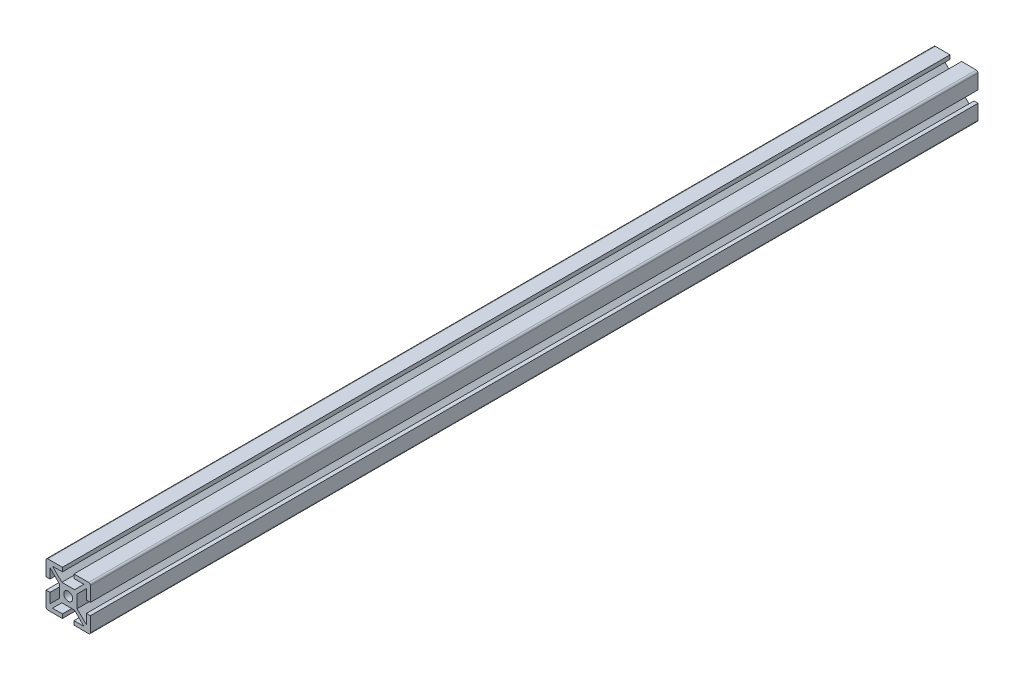
SolidWorks part; units mm, degrees
ref_plane "Front Plane" through (0, 0, 0) normal (0, 0, 1) x (1, 0, 0)
ref_plane "Top Plane" through (0, 0, 0) normal (0, 1, 0) x (1, 0, 0)
ref_plane "Right Plane" through (0, 0, 0) normal (1, 0, 0) x (0, 0, -1)
sketch "Sketch1" plane through (0, 0, 0) normal (0, 0, 1) x (1, 0, 0)
  line L0 (0, 17.7179) -> (0, -17.7179) construction
  line L1 (22.6216, 0) -> (-22.6216, 0) construction
  line L2 (-12.5, 12.5) -> (-12.5, 3.25)
  line L3 (-12.5, 3.25) -> (-10.25, 3.25)
  line L4 (-10.25, 3.25) -> (-10.25, 8.8358)
  line L5 (-10.25, 8.8358) -> (-5, 3.5858)
  line L6 (-5, 3.5858) -> (-5, -3.5858)
  line L9 (3.5858, 5) -> (-3.5858, 5)
  line L10 (-3.5858, 5) -> (-8.8358, 10.25)
  line L11 (-8.8358, 10.25) -> (-3.25, 10.25)
  line L12 (-3.25, 10.25) -> (-3.25, 12.5)
  line L13 (-3.25, 12.5) -> (-12.5, 12.5)
  line L14 (-12.5, 3.25) -> (-12.5, -3.25) construction
  line L15 (-3.25, 12.5) -> (3.25, 12.5) construction
  line L16 (-5, 3.5858) -> (-3.5858, 5) construction
  line L17 (5, 3.5858) -> (3.5858, 5) construction
  line L18 (12.5, 3.25) -> (12.5, -3.25) construction
  line L19 (3.25, 12.5) -> (12.5, 12.5)
  line L20 (3.25, 10.25) -> (3.25, 12.5)
  line L21 (8.8358, 10.25) -> (3.25, 10.25)
  line L22 (3.5858, 5) -> (8.8358, 10.25)
  line L23 (5, 3.5858) -> (5, -3.5858)
  line L24 (10.25, 8.8358) -> (5, 3.5858)
  line L25 (10.25, 3.25) -> (10.25, 8.8358)
  line L26 (12.5, 3.25) -> (10.25, 3.25)
  line L27 (12.5, 12.5) -> (12.5, 3.25)
  line L28 (5, -3.5858) -> (3.5858, -5) construction
  line L29 (-5, -3.5858) -> (-3.5858, -5) construction
  line L30 (-3.25, -12.5) -> (3.25, -12.5) construction
  line L31 (12.5, -12.5) -> (12.5, -3.25)
  line L32 (12.5, -3.25) -> (10.25, -3.25)
  line L33 (10.25, -3.25) -> (10.25, -8.8358)
  line L34 (10.25, -8.8358) -> (5, -3.5858)
  line L35 (3.5858, -5) -> (8.8358, -10.25)
  line L36 (8.8358, -10.25) -> (3.25, -10.25)
  line L37 (3.25, -10.25) -> (3.25, -12.5)
  line L38 (3.25, -12.5) -> (12.5, -12.5)
  line L39 (-3.25, -12.5) -> (-12.5, -12.5)
  line L40 (-3.25, -10.25) -> (-3.25, -12.5)
  line L41 (-8.8358, -10.25) -> (-3.25, -10.25)
  line L42 (-3.5858, -5) -> (-8.8358, -10.25)
  line L43 (3.5858, -5) -> (-3.5858, -5)
  line L44 (-10.25, -8.8358) -> (-5, -3.5858)
  line L45 (-10.25, -3.25) -> (-10.25, -8.8358)
  line L46 (-12.5, -3.25) -> (-10.25, -3.25)
  line L47 (-12.5, -12.5) -> (-12.5, -3.25)
  circle A0 centre (0, 0) radius 2.5
  point P4 (0, 0)
  point P5 (0, 0)
  point P28 (0, 12.5)
  point P33 (0, 5)
  point P37 (12.5, 0)
  point P44 (-12.5, 0)
  point P46 (5, 0)
  point P51 (-5, 0)
  point P53 (0, -5)
  point P54 (0, -12.5)
  dimension "D5" = 2.5
  dimension "D1" = 2.25
  dimension "D2" = 12.5
  dimension "D3" = 3.25
  dimension "D4" = 2
  dimension "D6" = 5
extrude "Boss-Extrude1" add sketch "Sketch1" along normal blind 500
fillet "Fillet1" radius 1 4 edges at (-12.5, -12.5, 250) (12.5, -12.5, 250) (12.5, 12.5, 250) (-12.5, 12.5, 250)
ref_plane "Plane1" through (0, 0, 0) normal (1, 0, 0) x (0, 0, -1)
ref_plane "Plane2" through (0, 0, 0) normal (0, 1, 0) x (1, 0, 0)
